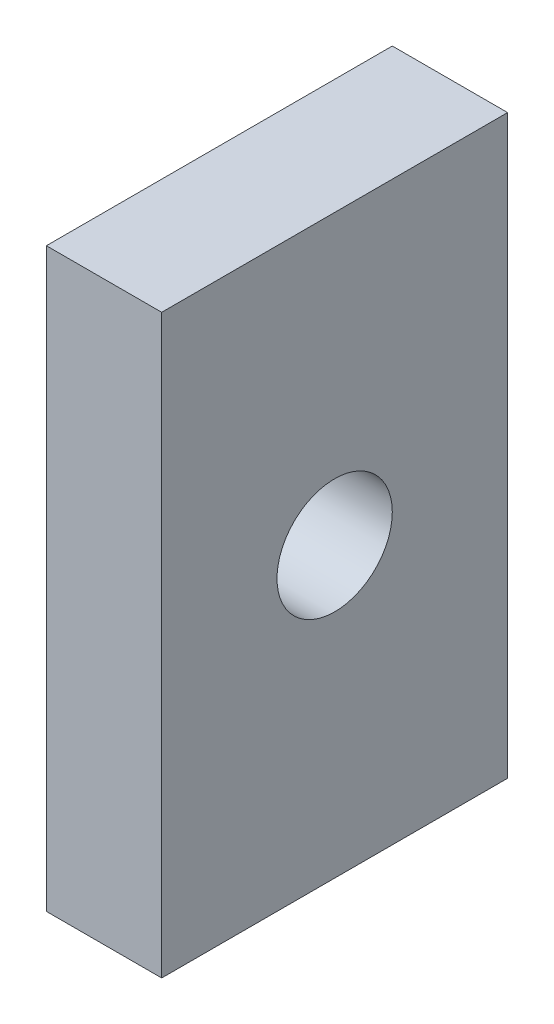
SolidWorks part; units mm, degrees
ref_plane "Alzado" through (0, 0, 0) normal (1, 0, 0) x (0, 1, 0)
ref_plane "Planta" through (0, 0, 0) normal (0, 0, 1) x (0, 1, 0)
ref_plane "Vista lateral" through (0, 0, 0) normal (0, 1, 0) x (-1, 0, 0)
sketch "Croquis2" plane through (0, 0, 0) normal (1, 0, 0) x (0, 1, 0)
  line L1 (-25, -15) -> (25, -15)
  line L2 (-25, -15) -> (-25, 15)
  line L3 (-25, 15) -> (25, 15)
  line L4 (25, -15) -> (25, 15)
  line L5 (-25, -15) -> (25, 15) construction
  line L6 (-25, 15) -> (25, -15) construction
  point P0 (0, 0)
extrude "Saliente-Extruir1" add sketch "Croquis2" along normal blind 10
sketch "Croquis3" plane through (10, 0, 0) normal (1, 0, 0) x (0, 1, 0)
  circle A0 centre (0, 0) radius 5
extrude "Cortar-Extruir1" cut sketch "Croquis3" against normal through all
